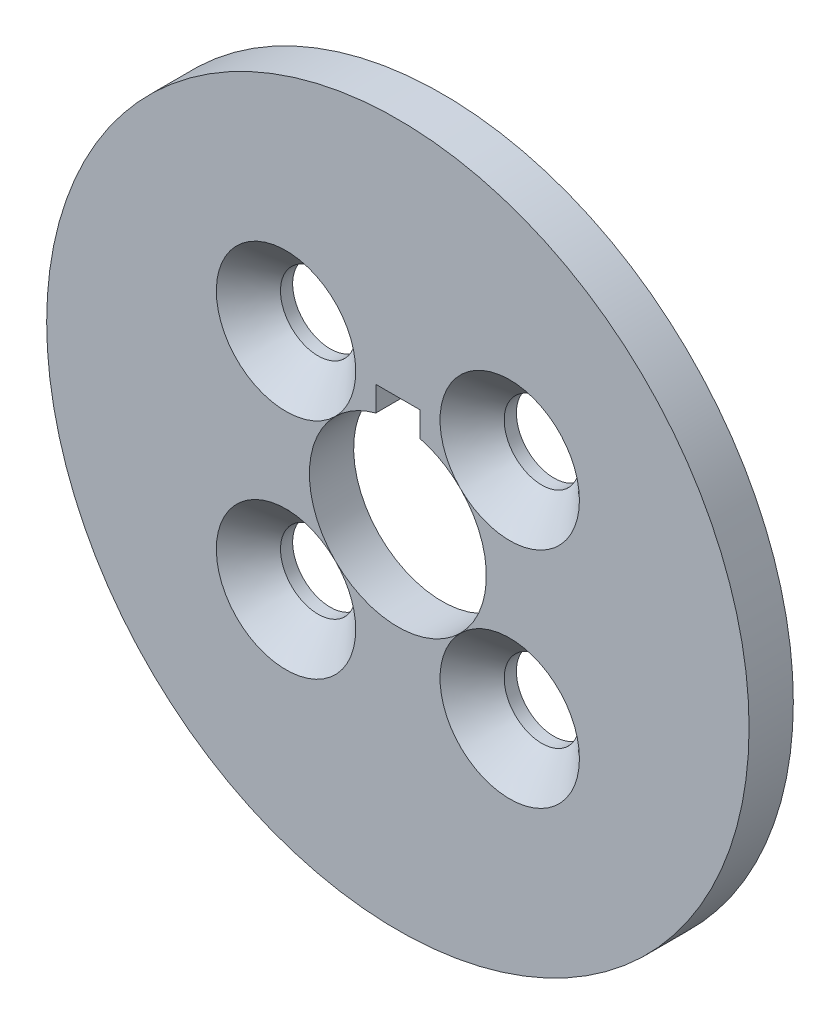
SolidWorks part; units mm, degrees
material "6061 Alloy"
ref_plane "Front" through (0, 0, 0) normal (0, 0, 1) x (1, 0, 0)
ref_plane "Top" through (0, 0, 0) normal (0, 1, 0) x (1, 0, 0)
ref_plane "Right" through (0, 0, 0) normal (1, 0, 0) x (0, 0, -1)
ref_plane "Plane1" through (0, 98.8856, 0) normal (0, -1, 0) x (1, 0, 0)
sketch "Sketch1" plane through (0, 98.8856, 0) normal (0, -1, 0) x (1, 0, 0)
  line L0 (-144.7318, 2) -> (-160.6068, 2)
  line L1 (-160.6068, 2) -> (-160.6068, 0)
  line L2 (-160.6068, 0) -> (-144.7318, 0)
  line L3 (-144.7318, 0) -> (-144.7318, 2)
  line L4 (-160.6068, 2) -> (-160.6068, 0) construction
revolve "Revolve1" add sketch "Sketch1" angle 360 about L4
sketch "Sketch2" plane through (0, 0, 0) normal (0, 0, -1) x (-1, 0, 0)
  line L0 (161.6068, 103.8856) -> (159.6068, 103.8856)
  line L1 (159.6068, 103.8856) -> (159.6068, 102.7586)
  line L2 (161.6068, 102.7586) -> (161.6068, 103.8856)
  arc A0 (159.6068, 102.7586) -> (161.6068, 102.7586) centre (160.6068, 98.8856) cw
  circle A1 centre (160.6068, 98.8856) radius 15.875 construction
  dimension "D1" = 4
  dimension "D2" = 2
  dimension "D3" = 5
  dimension "D4" = 1
extrude "Cut-Extrude1" cut sketch "Sketch2" against normal through all
ref_plane "Plane2" through (0, 98.8856, 0) normal (0, 1, 0) x (1, 0, 0)
sketch "Sketch3" plane through (0, 98.8856, 0) normal (0, 1, 0) x (1, 0, 0)
  line L0 (-156.6068, 0) -> (-160.6068, 0)
  line L1 (-160.6068, 0) -> (-160.6068, -2)
  line L2 (-160.6068, -2) -> (-156.6068, -2)
  line L3 (-156.6068, -2) -> (-156.6068, 0)
  line L4 (-160.6068, 0) -> (-160.6068, -2) construction
revolve "Cut-Revolve1" cut sketch "Sketch3" angle 360 about L4
hole_wizard "CSK for M3 Flat Head Machine Screw1" positions "Sketch5" profile "Sketch4" countersink size "M3" standard "ANSI Metric" end condition through all
sketch "Sketch5" plane through (0, 0, 2) normal (0, 0, 1) x (1, 0, 0)
  point P0 (-165.6626, 103.9414)
  point P1 (-155.5509, 103.9414)
  point P2 (-155.5509, 93.8298)
  point P3 (-165.6626, 93.8298)
sketch "Sketch4" plane through (-165.6626, 103.9414, 2) normal (1, 0, 0) x (0, -1, 0)
  line L0 (0, 0) -> (0, 2)
  line L1 (0, 2) -> (1.7, 2)
  line L2 (1.7, 2) -> (1.7, 1.45)
  line L3 (1.7, 1.45) -> (3.15, 0)
  line L5 (3.15, 0) -> (0, 0)
  line L6 (-1.7, 1.45) -> (-3.15, 0) construction
  line L11 (0, -6.35) -> (0, 107.95) construction
  dimension "Thru Hole Dia." = 3.4
  dimension "Thru Hole Depth" = 2
  dimension "Near C'Sink Dia." = 6.3
  dimension "Near C'Sink Angle" = 90
